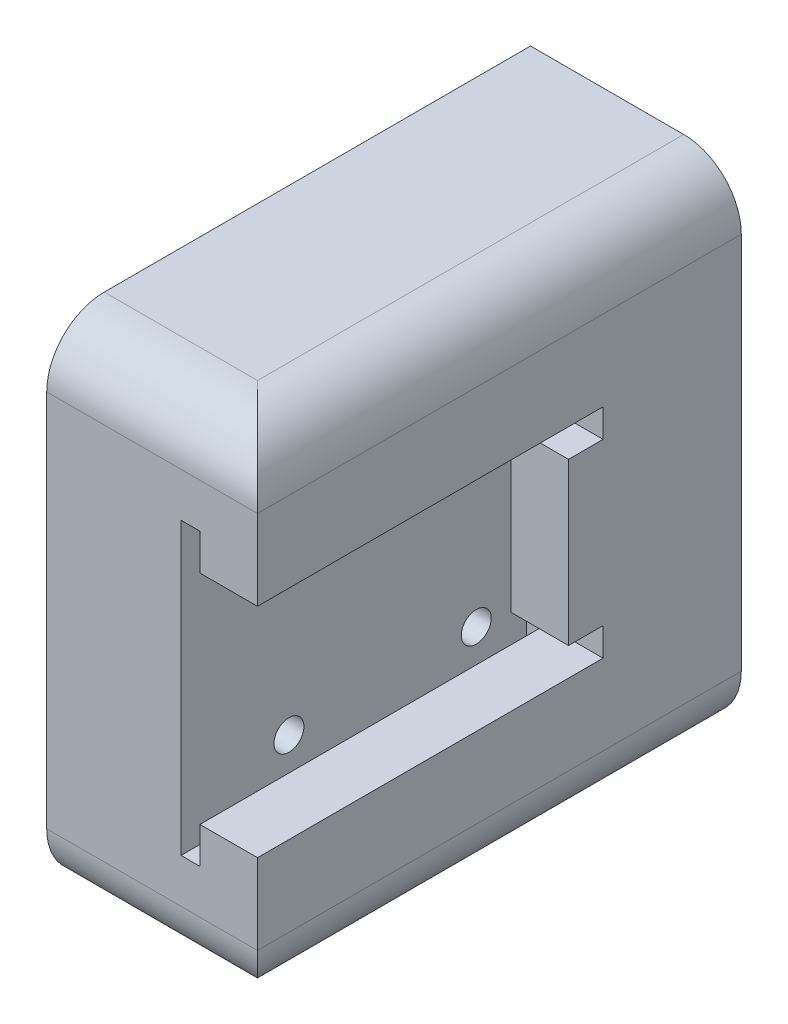
SolidWorks part; units mm, degrees
ref_plane "前视基准面" through (0, 0, 0) normal (0, 0, 1) x (1, 0, 0)
ref_plane "上视基准面" through (0, 0, 0) normal (0, 1, 0) x (1, 0, 0)
ref_plane "右视基准面" through (0, 0, 0) normal (1, 0, 0) x (0, 0, -1)
sketch "草图1" plane through (0, 0, 0) normal (0, 0, 1) x (1, 0, 0)
  line L0 (9.15, 0) -> (9.15, -20.4612) construction
  line L1 (0, 0) -> (18.3, 0)
  line L2 (0, 0) -> (0, -42.85)
  line L3 (0, -42.85) -> (18.3, -42.85)
  line L4 (18.3, 0) -> (18.3, -42.85)
  circle A0 centre (5.15, -5) radius 1.55
  circle A1 centre (5.15, -37.96) radius 1.55
  circle A2 centre (13.15, -37.96) radius 1.55
  circle A3 centre (13.15, -5) radius 1.55
  dimension "D7" = 3.1
  dimension "D8" = 3.1
  dimension "D1" = 42.85
  dimension "D2" = 18.3
  dimension "D3" = 4
  dimension "D4" = 5
  dimension "D5" = 32.96
  dimension "D6" = 4
extrude "凸台-拉伸1" add sketch "草图1" along normal blind 7
sketch "草图2" plane through (0, 0, 7) normal (0, 0, 1) x (1, 0, 0)
  line L0 (0, -42.85) -> (18.3, -42.85) construction
  line L5 (0, -21.425) -> (25.711, -21.425) construction
  line L6 (18.3, 0) -> (0, 0) construction
  line L7 (18.3, -42.85) -> (18.3, 0) construction
  line L12 (13.3, -14.425) -> (18.3, -14.425)
  line L13 (13.3, -14.425) -> (13.3, -28.425)
  line L14 (13.3, -28.425) -> (18.3, -28.425)
  line L15 (18.3, -14.425) -> (18.3, -28.425)
  dimension "D1" = 5
  dimension "D2" = 14
extrude "凸台-拉伸4" add sketch "草图2" along normal blind 8
sketch "草图5" plane through (0, 0, 7) normal (0, 0, 1) x (1, 0, 0)
  line L0 (18.3, -42.85) -> (18.3, -28.425) construction
  line L1 (13.3, -30.875) -> (18.3, -30.875)
  line L2 (13.3, -30.875) -> (13.3, -34.025)
  line L3 (13.3, -34.025) -> (18.3, -34.025)
  line L4 (18.3, -30.875) -> (18.3, -34.025)
  line L5 (0, -21.425) -> (28.7886, -21.425) construction
  line L7 (18.3, 0) -> (0, 0) construction
  line L8 (0, -42.85) -> (18.3, -42.85) construction
  line L9 (18.3, -11.975) -> (18.3, -8.825)
  line L10 (13.3, -8.825) -> (18.3, -8.825)
  line L11 (13.3, -11.975) -> (13.3, -8.825)
  line L12 (13.3, -11.975) -> (18.3, -11.975)
  dimension "D1" = 12.6
  dimension "D2" = 5
  dimension "D3" = 3.15
  dimension "D4" = 3.15
extrude "凸台-拉伸5" add sketch "草图5" along normal blind 35
sketch "草图7" plane through (0, 0, 7) normal (0, 0, 1) x (1, 0, 0)
  line L0 (18.3, 0) -> (0, 0) construction
  line L1 (0, 0) -> (12.7, 0)
  line L2 (0, 0) -> (0, -42.85)
  line L3 (0, -42.85) -> (12.7, -42.85)
  line L4 (11.66, -8.825) -> (11.66, -34.025)
  line L5 (0, -42.85) -> (18.3, -42.85) construction
  line L6 (13.3, -8.825) -> (13.3, -11.975) construction
  line L7 (18.3, -8.825) -> (13.3, -8.825) construction
  line L8 (18.3, -34.025) -> (11.66, -34.025)
  line L9 (18.3, -34.025) -> (18.3, -42.85)
  line L10 (18.3, -42.85) -> (12.7, -42.85)
  line L12 (18.3, 0) -> (12.7, 0)
  line L13 (18.3, 0) -> (18.3, -8.825)
  line L14 (18.3, -8.825) -> (11.66, -8.825)
  dimension "D1" = 1.64
extrude "凸台-拉伸7" add sketch "草图7" along normal blind 35
sketch "草图8" plane through (0, 0, 7) normal (0, 0, 1) x (1, 0, 0)
  line L0 (13.3, -30.875) -> (13.3, -34.025)
  line L1 (11.66, -8.825) -> (13.3, -8.825)
  line L2 (11.66, -8.825) -> (11.66, -34.025)
  line L3 (11.66, -34.025) -> (13.3, -34.025)
  line L4 (13.3, -8.825) -> (13.3, -11.975)
  line L5 (13.3, -11.975) -> (18.3, -11.975)
  line L7 (13.3, -14.425) -> (18.3, -14.425)
  line L8 (18.3, -11.975) -> (18.3, -14.425)
  line L9 (13.3, -28.425) -> (18.3, -28.425)
  line L11 (13.3, -30.875) -> (18.3, -30.875)
  line L12 (18.3, -28.425) -> (18.3, -30.875)
  line L13 (13.3, -14.425) -> (13.3, -28.425)
extrude "凸台-拉伸8" add sketch "草图8" along normal blind 5
sketch "草图9" plane through (11.66, 0, 0) normal (1, 0, 0) x (0, 0, -1)
  line L0 (-42, -8.825) -> (-12, -8.825) construction
  line L1 (-12, -28.425) -> (-12, -14.425) construction
  line L2 (-38, -21.425) -> (-35.0353, -21.425) construction
  line L4 (-42, -34.025) -> (-12, -34.025) construction
  circle A0 centre (-16.37, -13.195) radius 1.3
  circle A1 centre (-16.37, -29.655) radius 1.3
  circle A2 centre (-32.63, -13.195) radius 1.3
  circle A3 centre (-32.63, -29.655) radius 1.3
  dimension "D3" = 2.6
  dimension "D5" = 2.6
  dimension "D1" = 4.37
  dimension "D2" = 4.37
  dimension "D4" = 16.26
extrude "切除-拉伸1" cut sketch "草图9" against normal up to next
sketch "草图11" plane through (0, 0, 0) normal (0, 0, -1) x (-1, 0, 0)
  circle A0 centre (-13.15, -5) radius 1.55
  circle A1 centre (-5.15, -5) radius 1.55
  circle A2 centre (-5.15, -37.96) radius 1.55
  circle A3 centre (-13.15, -37.96) radius 1.55
extrude "切除-拉伸2" cut sketch "草图11" against normal blind 32
ref_plane "基准面1" through (0, 0, 25) normal (0, 0, 1) x (1, 0, 0)
sketch "草图12" plane through (0, 0, 25) normal (0, 0, 1) x (1, 0, 0)
  line L1 (16.15, -2) -> (10.15, -2)
  line L2 (16.15, -2) -> (16.15, -8)
  line L3 (16.15, -8) -> (10.15, -8)
  line L4 (10.15, -2) -> (10.15, -8)
  line L5 (16.15, -2) -> (10.15, -8) construction
  line L6 (16.15, -8) -> (10.15, -2) construction
  line L7 (8.15, -2) -> (2.15, -2)
  line L8 (8.15, -2) -> (8.15, -8)
  line L9 (8.15, -8) -> (2.15, -8)
  line L10 (2.15, -2) -> (2.15, -8)
  line L11 (8.15, -2) -> (2.15, -8) construction
  line L12 (8.15, -8) -> (2.15, -2) construction
  line L13 (16.15, -34.96) -> (10.15, -34.96)
  line L14 (16.15, -34.96) -> (16.15, -40.96)
  line L15 (16.15, -40.96) -> (10.15, -40.96)
  line L16 (10.15, -34.96) -> (10.15, -40.96)
  line L17 (16.15, -34.96) -> (10.15, -40.96) construction
  line L18 (16.15, -40.96) -> (10.15, -34.96) construction
  line L19 (8.15, -34.96) -> (2.15, -34.96)
  line L20 (8.15, -34.96) -> (8.15, -40.96)
  line L21 (8.15, -40.96) -> (2.15, -40.96)
  line L22 (2.15, -34.96) -> (2.15, -40.96)
  line L23 (8.15, -34.96) -> (2.15, -40.96) construction
  line L24 (8.15, -40.96) -> (2.15, -34.96) construction
  point P0 (13.15, -5)
  point P6 (5.15, -5)
  point P12 (13.15, -37.96)
  point P18 (5.15, -37.96)
  dimension "D1" = 6
  dimension "D2" = 6
  dimension "D3" = 6
  dimension "D4" = 6
  dimension "D5" = 6
  dimension "D6" = 6
  dimension "D7" = 6
  dimension "D8" = 6
extrude "切除-拉伸3" cut sketch "草图12" against normal blind 3.2
fillet "圆角1" radius 5 4 edges at (9.15, -42.85, 42) (9.15, 0, 42) (18.3, -42.85, 21) (18.3, 0, 21)
